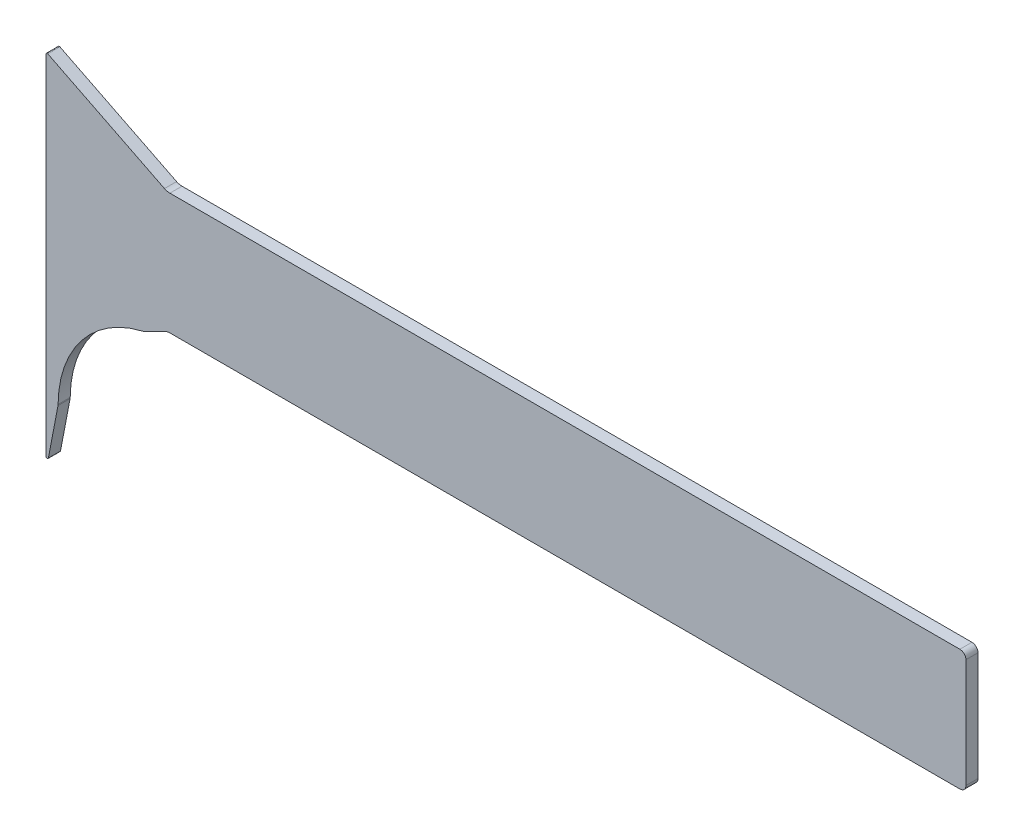
SolidWorks part; units mm, degrees
ref_plane "Front Plane" through (0, 0, 0) normal (0, 0, 1) x (1, 0, 0)
ref_plane "Top Plane" through (0, 0, 0) normal (0, 1, 0) x (1, 0, 0)
ref_plane "Right Plane" through (0, 0, 0) normal (1, 0, 0) x (0, 0, -1)
sketch "Sketch1" plane through (0, 0, 0) normal (0, 0, 1) x (1, 0, 0)
  line L0 (1.4472, 99.2764) -> (97.8885, 51.0557)
  line L2 (100, 50) -> (100, -50) construction
  line L3 (600, -40) -> (0, -40) construction
  line L4 (102.3607, -50) -> (755, -50)
  line L5 (600, -50) -> (0, -50) construction
  line L6 (0, -190) -> (0, 90) construction
  line L7 (10, -52.9377) -> (10, -147.7496) construction
  line L8 (760, -45) -> (760, 45)
  line L9 (9.9121, -148.209) -> (1.9822, -189.6431)
  line L10 (0, -189.4551) -> (0, 98.382)
  line L11 (755, 50) -> (102.3607, 50)
  line L12 (80, -40) -> (80, -60) construction
  line L13 (97.8885, -51.0557) -> (80.5309, -59.7346)
  arc A0 (79.4372, -60.1302) -> (10.0012, -147.2944) centre (100, -147.7496) ccw
  arc A1 (1.9822, -189.6431) -> (0, -189.4551) centre (1, -189.4551) cw
  arc A2 (1.4472, 99.2764) -> (0, 98.382) centre (1, 98.382) ccw
  arc A3 (10.0012, -147.2944) -> (9.9121, -148.209) centre (5.0012, -147.2691) cw
  arc A4 (79.4372, -60.1302) -> (80.5309, -59.7346) centre (78.2948, -55.2624) ccw
  arc A5 (97.8885, -51.0557) -> (102.3607, -50) centre (102.3607, -60) cw
  arc A6 (97.8885, 51.0557) -> (102.3607, 50) centre (102.3607, 60) ccw
  arc A7 (760, 45) -> (755, 50) centre (755, 45) ccw
  arc A8 (755, -50) -> (760, -45) centre (755, -45) ccw
  point P21 (0, -200)
  point P24 (0, 100)
  dimension "D3" = 1
  dimension "D4" = 5
  dimension "D5" = 100
  dimension "D6" = 5
  dimension "D7" = 10
  dimension "D8" = 5
  dimension "D1" = 10
  dimension "D2" = 10
extrude "Boss-Extrude1" add sketch "Sketch1" along normal blind 10
